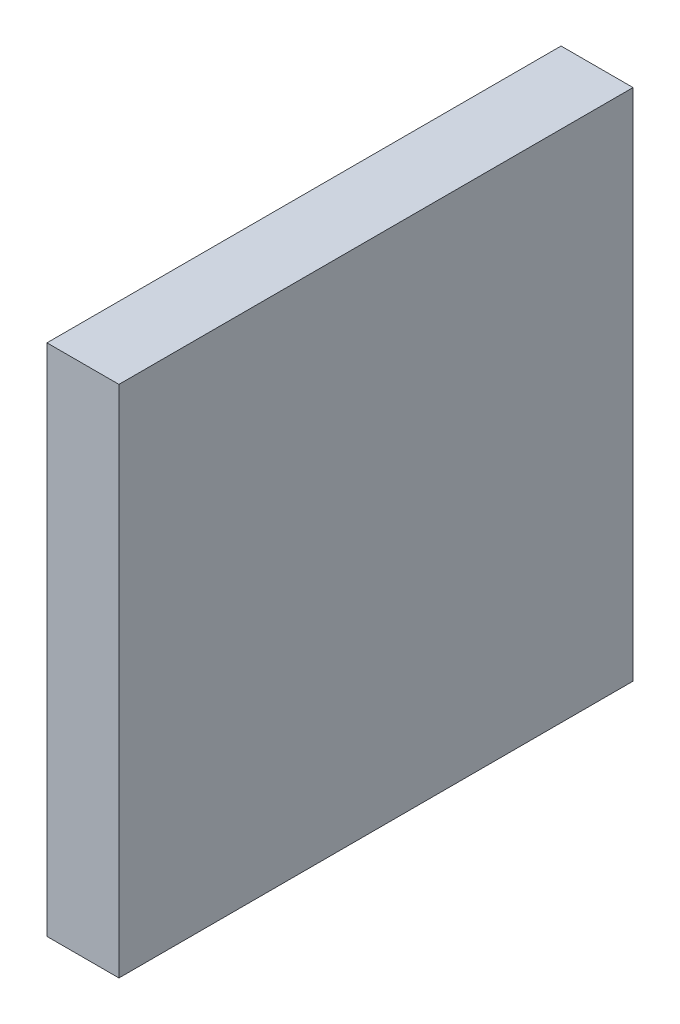
SolidWorks part; units mm, degrees
ref_plane "Front Plane" through (0, 0, 0) normal (0, 0, 1) x (1, 0, 0)
ref_plane "Top Plane" through (0, 0, 0) normal (0, 1, 0) x (1, 0, 0)
ref_plane "Right Plane" through (0, 0, 0) normal (1, 0, 0) x (0, 0, -1)
ref_plane "PL_Box_0_base" through (0, 0, 100) normal (0, 0, 1) x (1, 0, 0)
sketch "SK_Box_0" plane through (0, 0, 100) normal (0, 0, 1) x (1, 0, 0)
  line L0 (32, -50) -> (46, -50)
  line L1 (46, -50) -> (46, 50)
  line L2 (46, 50) -> (32, 50)
  line L3 (32, 50) -> (32, -50)
  dimension "P1" = 32
  dimension "P2" = 50
  dimension "P3" = 46
  dimension "P4" = 50
  dimension "P5" = 46
  dimension "P6" = 50
  dimension "P7" = 32
  dimension "P8" = 50
extrude "Box_0" add sketch "SK_Box_0" along normal blind 100
